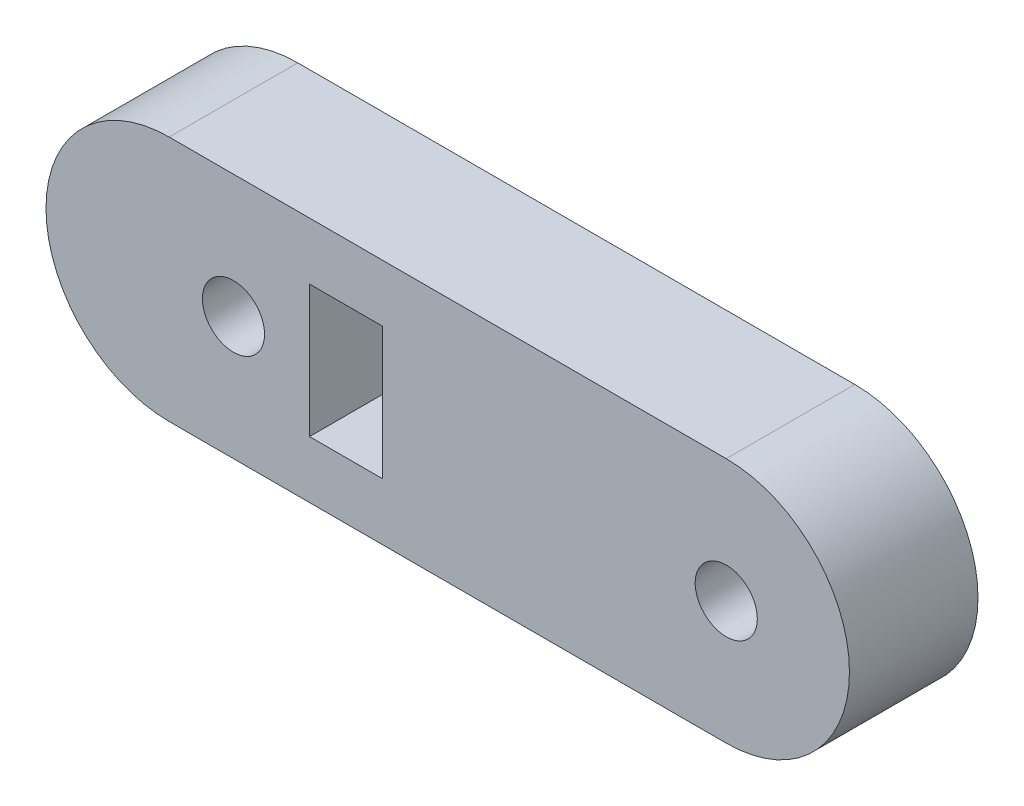
SolidWorks part; units mm, degrees
material "Acrylic (Medium-high impact)"
ref_plane "Front Plane" through (0, 0, 0) normal (0, 0, 1) x (1, 0, 0)
ref_plane "Top Plane" through (0, 0, 0) normal (0, 1, 0) x (1, 0, 0)
ref_plane "Right Plane" through (0, 0, 0) normal (1, 0, 0) x (0, 0, -1)
sketch "Sketch1" plane through (0, 0, 0) normal (0, 0, 1) x (1, 0, 0)
  line L0 (595.0214, 463.5654) -> (595.0214, 460.4829) construction
  line L1 (595.0214, 460.4829) -> (595.0214, 457.4004) construction
  line L2 (596.7214, 463.5654) -> (596.7214, 457.4004)
  line L3 (596.7214, 457.4004) -> (593.3214, 457.4004)
  line L4 (593.3214, 457.4004) -> (593.3214, 463.5654)
  line L5 (593.3214, 463.5654) -> (596.7214, 463.5654)
  line L6 (595.0214, 463.5654) -> (595.0214, 466.2329) construction
  line L7 (589.7714, 460.4829) -> (589.7714, 466.2329) construction
  line L8 (589.7714, 460.4829) -> (589.7714, 454.7329) construction
  line L9 (612.7714, 460.4829) -> (612.7714, 466.2329) construction
  line L10 (612.7714, 460.4829) -> (612.7714, 454.7329) construction
  line L11 (589.7714, 466.2329) -> (612.7714, 466.2329)
  line L12 (589.7714, 454.7329) -> (612.7714, 454.7329)
  line L13 (593.3214, 460.4829) -> (595.0214, 460.4829) construction
  line L14 (595.0214, 460.4829) -> (596.7214, 460.4829) construction
  line L15 (589.7714, 460.4829) -> (595.0214, 460.4829) construction
  line L16 (612.7714, 460.4829) -> (595.0214, 460.4829) construction
  line L17 (595.0214, 460.4829) -> (589.7714, 460.4829) construction
  line L18 (589.7714, 466.2329) -> (586.7714, 466.2329)
  line L19 (589.7714, 454.7329) -> (586.7714, 454.7329)
  circle A0 centre (589.7714, 460.4829) radius 1.45
  circle A1 centre (612.7714, 460.4829) radius 1.45
  arc A2 (586.7714, 466.2329) -> (586.7714, 454.7329) centre (586.7714, 460.4829) ccw
  arc A3 (612.7714, 454.7329) -> (612.7714, 466.2329) centre (612.7714, 460.4829) ccw
  point P19 (591.2214, 460.4829)
  dimension "D1" = 2.1
  dimension "D2" = 2.9
  dimension "D3" = 23
  dimension "D4" = 11.5
  dimension "D5" = 3.4
  dimension "D6" = 6.165
  dimension "D7" = 3
extrude "Boss-Extrude1" add sketch "Sketch1" along normal blind 6
